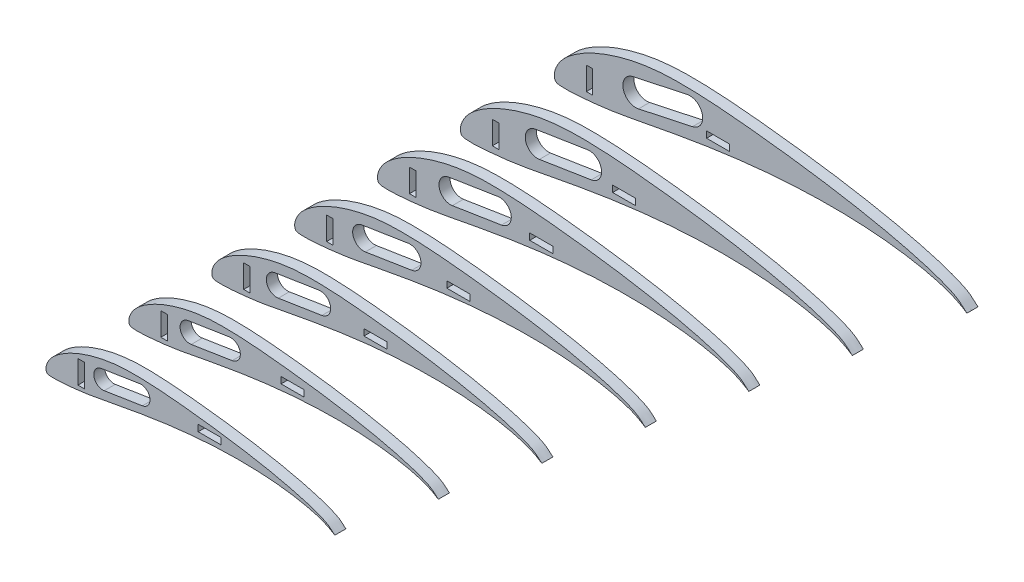
SolidWorks part; units mm, degrees
material "Balsa"
ref_plane "Front Plane" through (0, 0, 0) normal (1, 0, 0) x (0, 1, 0)
ref_plane "Top Plane" through (0, 0, 0) normal (0, 0, 1) x (0, 1, 0)
ref_plane "Right Plane" through (0, 0, 0) normal (0, 1, 0) x (-1, 0, 0)
curve "Curve1"
  spline degree 3 poles (0.9961, 0.0026, 0) (1.0009, -0.0006, 0) (0.9967, 0.0025, 0) (0.9939, 0.0052, 0) (0.9878, 0.0109, 0) (0.9805, 0.017, 0) (0.9705, 0.0231, 0) (0.9581, 0.029, 0) (0.9432, 0.0352, 0) (0.9257, 0.0415, 0) (0.9057, 0.048, 0) (0.8834, 0.0546, 0) (0.8588, 0.0611, 0) (0.8322, 0.0677, 0) (0.8036, 0.0742, 0) (0.7732, 0.0806, 0) (0.7412, 0.0869, 0) (0.7079, 0.0929, 0) (0.6733, 0.0987, 0) (0.6378, 0.1042, 0) (0.6014, 0.1094, 0) (0.5646, 0.1143, 0) (0.5275, 0.1189, 0) (0.4904, 0.1231, 0) (0.4536, 0.1269, 0) (0.4175, 0.1302, 0) (0.3823, 0.1328, 0) (0.3482, 0.1346, 0) (0.3154, 0.1354, 0) (0.284, 0.1353, 0) (0.2541, 0.1338, 0) (0.2258, 0.1307, 0) (0.1988, 0.1263, 0) (0.1732, 0.1206, 0) (0.1489, 0.1139, 0) (0.1262, 0.1063, 0) (0.1051, 0.0981, 0) (0.0858, 0.0892, 0) (0.0682, 0.0798, 0) (0.0525, 0.0701, 0) (0.0388, 0.0602, 0) (0.0271, 0.0502, 0) (0.0176, 0.0401, 0) (0.0103, 0.03, 0) (0.0049, 0.0202, 0) (0.0014, 0.0108, 0) (-0.0002, 0.0022, 0) (0.0001, -0.0051, 0) (0.002, -0.0118, 0) (0.0089, -0.0151, 0) (0.0183, -0.0156, 0) (0.0312, -0.016, 0) (0.0473, -0.0153, 0) (0.0666, -0.0141, 0) (0.0888, -0.012, 0) (0.1137, -0.0092, 0) (0.1411, -0.0057, 0) (0.1711, -0.0007, 0) (0.2038, 0.0055, 0) (0.2393, 0.0123, 0) (0.2775, 0.0195, 0) (0.3182, 0.0267, 0) (0.361, 0.0338, 0) (0.4056, 0.0404, 0) (0.4517, 0.0464, 0) (0.4987, 0.0515, 0) (0.5464, 0.0555, 0) (0.5941, 0.0584, 0) (0.6414, 0.06, 0) (0.6878, 0.0602, 0) (0.7328, 0.059, 0) (0.7758, 0.0564, 0) (0.8164, 0.0525, 0) (0.854, 0.0475, 0) (0.8881, 0.0414, 0) (0.9184, 0.0345, 0) (0.9444, 0.027, 0) (0.9656, 0.0191, 0) (0.9807, 0.0119, 0) (0.9918, 0.0052, 0) (0.9961, 0.0026, 0) (1.0009, -0.0006, 0) (0.9967, 0.0025, 0) knots -0.009748 -0.004147 -0.001 0 0.00098 0.003649 0.007483 0.012095 0.017526 0.024052 0.031783 0.040678 0.05071 0.061833 0.073989 0.087118 0.101145 0.115991 0.13157 0.147788 0.164551 0.181758 0.199312 0.217095 0.23499 0.252857 0.270541 0.287887 0.304773 0.321101 0.336806 0.3518 0.366031 0.379616 0.392653 0.40517 0.417172 0.428604 0.439419 0.449597 0.459102 0.467908 0.475988 0.483309 0.489875 0.495803 0.501149 0.505903 0.510047 0.513579 0.516447 0.51935 0.523823 0.529974 0.537716 0.546968 0.557637 0.56962 0.582804 0.597247 0.613135 0.630444 0.649056 0.668822 0.689595 0.71119 0.733427 0.756094 0.778989 0.80189 0.824567 0.846792 0.868338 0.888978 0.908492 0.926659 0.943286 0.958169 0.971136 0.981956 0.990252 0.995853 0.999 1 1.00098 1.003649 1.007483 periodic
sketch "Sketch2" plane through (0, 0, 0) normal (0, 0, 1) x (0, 1, 0)
  spline S0 degree 3 poles (0.0026, -0.9961) (-0.0006, -1.0009) (0.0025, -0.9967) (0.0052, -0.9939) (0.0109, -0.9878) (0.017, -0.9805) (0.0231, -0.9705) (0.029, -0.9581) (0.0352, -0.9432) (0.0415, -0.9257) (0.048, -0.9057) (0.0546, -0.8834) (0.0611, -0.8588) (0.0677, -0.8322) (0.0742, -0.8036) (0.0806, -0.7732) (0.0869, -0.7412) (0.0929, -0.7079) (0.0987, -0.6733) (0.1042, -0.6378) (0.1094, -0.6014) (0.1143, -0.5646) (0.1189, -0.5275) (0.1231, -0.4904) (0.1269, -0.4536) (0.1302, -0.4175) (0.1328, -0.3823) (0.1346, -0.3482) (0.1354, -0.3154) (0.1353, -0.284) (0.1338, -0.2541) (0.1307, -0.2258) (0.1263, -0.1988) (0.1206, -0.1732) (0.1139, -0.1489) (0.1063, -0.1262) (0.0981, -0.1051) (0.0892, -0.0858) (0.0798, -0.0682) (0.0701, -0.0525) (0.0602, -0.0388) (0.0502, -0.0271) (0.0401, -0.0176) (0.03, -0.0103) (0.0202, -0.0049) (0.0108, -0.0014) (0.0022, 0.0002) (-0.0051, -0.0001) (-0.0118, -0.002) (-0.0151, -0.0089) (-0.0156, -0.0183) (-0.016, -0.0312) (-0.0153, -0.0473) (-0.0141, -0.0666) (-0.012, -0.0888) (-0.0092, -0.1137) (-0.0057, -0.1411) (-0.0007, -0.1711) (0.0055, -0.2038) (0.0123, -0.2393) (0.0195, -0.2775) (0.0267, -0.3182) (0.0338, -0.361) (0.0404, -0.4056) (0.0464, -0.4517) (0.0515, -0.4987) (0.0555, -0.5464) (0.0584, -0.5941) (0.06, -0.6414) (0.0602, -0.6878) (0.059, -0.7328) (0.0564, -0.7758) (0.0525, -0.8164) (0.0475, -0.854) (0.0414, -0.8881) (0.0345, -0.9184) (0.027, -0.9444) (0.0191, -0.9656) (0.0119, -0.9807) (0.0052, -0.9918) (0.0026, -0.9961) (-0.0006, -1.0009) (0.0025, -0.9967) knots -0.009748 -0.004147 -0.001 0 0.00098 0.003649 0.007483 0.012095 0.017526 0.024052 0.031783 0.040678 0.05071 0.061833 0.073989 0.087118 0.101145 0.115991 0.13157 0.147788 0.164551 0.181758 0.199312 0.217095 0.23499 0.252857 0.270541 0.287887 0.304773 0.321101 0.336806 0.3518 0.366031 0.379616 0.392653 0.40517 0.417172 0.428604 0.439419 0.449597 0.459102 0.467908 0.475988 0.483309 0.489875 0.495803 0.501149 0.505903 0.510047 0.513579 0.516447 0.51935 0.523823 0.529974 0.537716 0.546968 0.557637 0.56962 0.582804 0.597247 0.613135 0.630444 0.649056 0.668822 0.689595 0.71119 0.733427 0.756094 0.778989 0.80189 0.824567 0.846792 0.868338 0.888978 0.908492 0.926659 0.943286 0.958169 0.971136 0.981956 0.990252 0.995853 0.999 1 1.00098 1.003649 1.007483 only from (0, -1) to (0, -1) construction
  spline S1 degree 3 poles (0.0026, -0.9961) (-0.0006, -1.0009) (0.0025, -0.9967) (0.0052, -0.9939) (0.0109, -0.9878) (0.017, -0.9805) (0.0231, -0.9705) (0.029, -0.9581) (0.0352, -0.9432) (0.0415, -0.9257) (0.048, -0.9057) (0.0546, -0.8834) (0.0611, -0.8588) (0.0677, -0.8322) (0.0742, -0.8036) (0.0806, -0.7732) (0.0869, -0.7412) (0.0929, -0.7079) (0.0987, -0.6733) (0.1042, -0.6378) (0.1094, -0.6014) (0.1143, -0.5646) (0.1189, -0.5275) (0.1231, -0.4904) (0.1269, -0.4536) (0.1302, -0.4175) (0.1328, -0.3823) (0.1346, -0.3482) (0.1354, -0.3154) (0.1353, -0.284) (0.1338, -0.2541) (0.1307, -0.2258) (0.1263, -0.1988) (0.1206, -0.1732) (0.1139, -0.1489) (0.1063, -0.1262) (0.0981, -0.1051) (0.0892, -0.0858) (0.0798, -0.0682) (0.0701, -0.0525) (0.0602, -0.0388) (0.0502, -0.0271) (0.0401, -0.0176) (0.03, -0.0103) (0.0202, -0.0049) (0.0108, -0.0014) (0.0022, 0.0002) (-0.0051, -0.0001) (-0.0118, -0.002) (-0.0151, -0.0089) (-0.0156, -0.0183) (-0.016, -0.0312) (-0.0153, -0.0473) (-0.0141, -0.0666) (-0.012, -0.0888) (-0.0092, -0.1137) (-0.0057, -0.1411) (-0.0007, -0.1711) (0.0055, -0.2038) (0.0123, -0.2393) (0.0195, -0.2775) (0.0267, -0.3182) (0.0338, -0.361) (0.0404, -0.4056) (0.0464, -0.4517) (0.0515, -0.4987) (0.0555, -0.5464) (0.0584, -0.5941) (0.06, -0.6414) (0.0602, -0.6878) (0.059, -0.7328) (0.0564, -0.7758) (0.0525, -0.8164) (0.0475, -0.854) (0.0414, -0.8881) (0.0345, -0.9184) (0.027, -0.9444) (0.0191, -0.9656) (0.0119, -0.9807) (0.0052, -0.9918) (0.0026, -0.9961) (-0.0006, -1.0009) (0.0025, -0.9967) knots -0.009748 -0.004147 -0.001 0 0.00098 0.003649 0.007483 0.012095 0.017526 0.024052 0.031783 0.040678 0.05071 0.061833 0.073989 0.087118 0.101145 0.115991 0.13157 0.147788 0.164551 0.181758 0.199312 0.217095 0.23499 0.252857 0.270541 0.287887 0.304773 0.321101 0.336806 0.3518 0.366031 0.379616 0.392653 0.40517 0.417172 0.428604 0.439419 0.449597 0.459102 0.467908 0.475988 0.483309 0.489875 0.495803 0.501149 0.505903 0.510047 0.513579 0.516447 0.51935 0.523823 0.529974 0.537716 0.546968 0.557637 0.56962 0.582804 0.597247 0.613135 0.630444 0.649056 0.668822 0.689595 0.71119 0.733427 0.756094 0.778989 0.80189 0.824567 0.846792 0.868338 0.888978 0.908492 0.926659 0.943286 0.958169 0.971136 0.981956 0.990252 0.995853 0.999 1 1.00098 1.003649 1.007483 only from (0, -1) to (0, -1)
  spline S2 degree 3 poles (0.5817, -223.1332) (-0.1446, -224.2031) (0.5543, -223.265) (1.1654, -222.6422) (2.4417, -221.2594) (3.7994, -219.628) (5.1681, -217.3965) (6.4946, -214.6215) (7.8789, -211.2714) (9.3018, -207.3514) (10.7532, -202.8797) (12.2206, -197.8796) (13.697, -192.379) (15.1689, -186.4082) (16.6256, -180.0017) (18.0581, -173.1974) (19.4589, -166.037) (20.8109, -158.5624) (22.1121, -150.8205) (23.3457, -142.856) (24.5142, -134.7205) (25.6083, -126.466) (26.6244, -118.1523) (27.5699, -109.846) (28.4208, -101.6157) (29.1612, -93.5286) (29.7494, -85.6414) (30.154, -77.9993) (30.3288, -70.6447) (30.3102, -63.6154) (29.966, -56.9245) (29.2685, -50.5693) (28.2823, -44.524) (27.0047, -38.7872) (25.5065, -33.3646) (23.8143, -28.2794) (21.9676, -23.553) (19.9763, -19.2149) (17.8809, -15.279) (15.7052, -11.7667) (13.4787, -8.7) (11.2485, -6.0802) (8.9904, -3.9452) (6.7238, -2.3053) (4.5187, -1.094) (2.4251, -0.3176) (0.4927, 0.0523) (-1.1416, -0.0191) (-2.6406, -0.4398) (-3.3847, -2.0039) (-3.4891, -4.1068) (-3.5903, -6.9836) (-3.4343, -10.6014) (-3.1476, -14.9192) (-2.6884, -19.8891) (-2.067, -25.4601) (-1.2702, -31.6052) (-0.1566, -38.3213) (1.2399, -45.641) (2.7597, -53.6011) (4.3644, -62.1626) (5.9874, -71.2717) (7.5678, -80.8615) (9.0528, -90.8576) (10.3879, -101.1739) (11.5342, -111.7177) (12.4404, -122.3892) (13.0827, -133.0814) (13.4358, -143.6827) (13.4805, -154.0779) (13.2135, -164.1512) (12.6412, -173.7872) (11.771, -182.8699) (10.6363, -191.2914) (9.27, -198.9419) (7.7178, -205.7317) (6.0569, -211.5357) (4.2843, -216.2857) (2.6621, -219.6747) (1.1621, -222.1733) (0.5817, -223.1332) (-0.1446, -224.2031) (0.5543, -223.265) knots -0.009748 -0.004147 -0.001 0 0.00098 0.003649 0.007483 0.012095 0.017526 0.024052 0.031783 0.040678 0.05071 0.061833 0.073989 0.087118 0.101145 0.115991 0.13157 0.147788 0.164551 0.181758 0.199312 0.217095 0.23499 0.252857 0.270541 0.287887 0.304773 0.321101 0.336806 0.3518 0.366031 0.379616 0.392653 0.40517 0.417172 0.428604 0.439419 0.449597 0.459102 0.467908 0.475988 0.483309 0.489875 0.495803 0.501149 0.505903 0.510047 0.513579 0.516447 0.51935 0.523823 0.529974 0.537716 0.546968 0.557637 0.56962 0.582804 0.597247 0.613135 0.630444 0.649056 0.668822 0.689595 0.71119 0.733427 0.756094 0.778989 0.80189 0.824567 0.846792 0.868338 0.888978 0.908492 0.926659 0.943286 0.958169 0.971136 0.981956 0.990252 0.995853 0.999 1 1.00098 1.003649 1.007483 only from (0, -224) to (0, -224)
extrude "Boss-Extrude1" add sketch "Sketch2" along normal blind 6 contours S2
sketch "Sketch3" plane through (0, 0, 0) normal (0, 0, -1) x (1, 0, 0)
  line L2 (58.8605, -3.7419) -> (58.8605, -30.0419) construction
  line L7 (44.1949, -13.7419) -> (73.526, -20.0419) construction
  line L8 (45.6649, -6.898) -> (74.996, -13.198)
  line L9 (42.7249, -20.5858) -> (72.056, -26.8858)
  arc A5 (45.6649, -6.898) -> (42.7249, -20.5858) centre (44.1949, -13.7419) ccw
  arc A6 (72.056, -26.8858) -> (74.996, -13.198) centre (73.526, -20.0419) ccw
  spline S0 degree 3 poles (223.265, -0.5543) (224.2031, 0.1446) (223.1332, -0.5817) (222.1733, -1.1621) (219.6747, -2.6621) (216.2857, -4.2843) (211.5357, -6.0569) (205.7317, -7.7178) (198.9419, -9.27) (191.2914, -10.6363) (182.8699, -11.771) (173.7872, -12.6412) (164.1512, -13.2135) (154.0779, -13.4805) (143.6827, -13.4358) (133.0814, -13.0827) (122.3892, -12.4404) (111.7177, -11.5342) (101.1739, -10.3879) (90.8576, -9.0528) (80.8615, -7.5678) (71.2717, -5.9874) (62.1626, -4.3644) (53.6011, -2.7597) (45.641, -1.2399) (38.3213, 0.1566) (31.6052, 1.2702) (25.4601, 2.067) (19.8891, 2.6884) (14.9192, 3.1476) (10.6014, 3.4343) (6.9836, 3.5903) (4.1068, 3.4891) (2.0039, 3.3847) (0.4398, 2.6406) (0.0191, 1.1416) (-0.0523, -0.4927) (0.3176, -2.4251) (1.094, -4.5187) (2.3053, -6.7238) (3.9452, -8.9904) (6.0802, -11.2485) (8.7, -13.4787) (11.7667, -15.7052) (15.279, -17.8809) (19.2149, -19.9763) (23.553, -21.9676) (28.2794, -23.8143) (33.3646, -25.5065) (38.7872, -27.0047) (44.524, -28.2823) (50.5693, -29.2685) (56.9245, -29.966) (63.6154, -30.3102) (70.6447, -30.3288) (77.9993, -30.154) (85.6414, -29.7494) (93.5286, -29.1612) (101.6157, -28.4208) (109.846, -27.5699) (118.1523, -26.6244) (126.466, -25.6083) (134.7205, -24.5142) (142.856, -23.3457) (150.8205, -22.1121) (158.5624, -20.8109) (166.037, -19.4589) (173.1974, -18.0581) (180.0017, -16.6256) (186.4082, -15.1689) (192.379, -13.697) (197.8796, -12.2206) (202.8797, -10.7532) (207.3514, -9.3018) (211.2714, -7.8789) (214.6215, -6.4946) (217.3965, -5.1681) (219.628, -3.7994) (221.2594, -2.4417) (222.6422, -1.1654) (223.265, -0.5543) (224.2031, 0.1446) (223.1332, -0.5817) knots -0.007483 -0.003649 -0.00098 0 0.001 0.004147 0.009748 0.018044 0.028864 0.041831 0.056714 0.073341 0.091508 0.111022 0.131662 0.153208 0.175433 0.19811 0.221011 0.243906 0.266573 0.28881 0.310405 0.331178 0.350944 0.369556 0.386865 0.402753 0.417196 0.43038 0.442363 0.453032 0.462284 0.470026 0.476177 0.48065 0.483553 0.486421 0.489953 0.494097 0.498851 0.504197 0.510125 0.516691 0.524012 0.532092 0.540898 0.550403 0.560581 0.571396 0.582828 0.59483 0.607347 0.620384 0.633969 0.6482 0.663194 0.678899 0.695227 0.712113 0.729459 0.747143 0.76501 0.782905 0.800688 0.818242 0.835449 0.852212 0.86843 0.884009 0.898855 0.912882 0.926011 0.938167 0.94929 0.959322 0.968217 0.975948 0.982474 0.987905 0.992517 0.996351 0.99902 1 1.001 1.004147 1.009748 only from (224, 0) to (224, 0) construction
  point P22 (58.8605, -16.8919)
  dimension "D1" = 10
  dimension "D3" = 30
  dimension "D9" = 7
  dimension "D4" = 26.3
extrude "Cut-Extrude1" cut sketch "Sketch3" against normal blind 10
sketch "Sketch4" plane through (0, 0, 0) normal (0, 0, -1) x (-1, 0, 0)
  point P0 (0, 0)
ref_plane "Plane1" through (-0.0039, 0, 0) normal (-0.9999, 0.0105, 0) x (0, 0, 1)
ref_plane "Plane2" through (0, 0, -45) normal (0, 0, -1) x (-1, 0, 0)
ref_plane "Plane3" through (0, 0, -90) normal (0, 0, -1) x (-1, 0, 0)
ref_plane "Plane4" through (0, 0, -135) normal (0, 0, -1) x (-1, 0, 0)
ref_plane "Plane5" through (0, 0, -180) normal (0, 0, -1) x (-1, 0, 0)
ref_plane "Plane6" through (0, 0, -225) normal (0, 0, -1) x (-1, 0, 0)
ref_plane "Plane7" through (0, 0, -270) normal (0, 0, -1) x (-1, 0, 0)
sketch "Sketch5" plane through (0, 0, -45) normal (0, 0, -1) x (-1, 0, 0)
  line L4 (-40.8046, 20.3934) -> (-68.9559, 24.8385)
  line L5 (-71.0302, 11.7013) -> (-42.879, 7.2561)
  arc A4 (-42.879, 7.2561) -> (-40.8046, 20.3934) centre (-41.8418, 13.8248) ccw
  arc A5 (-68.9559, 24.8385) -> (-71.0302, 11.7013) centre (-69.993, 18.2699) ccw
  spline S2 degree 3 poles (-212.1017, 0.5266) (-212.9929, -0.1374) (-211.9765, 0.5526) (-211.0646, 1.104) (-208.691, 2.529) (-205.4714, 4.0701) (-200.9589, 5.7541) (-195.4451, 7.3319) (-188.9948, 8.8065) (-181.7268, 10.1045) (-173.7264, 11.1825) (-165.0978, 12.0092) (-155.9436, 12.5528) (-146.374, 12.8064) (-136.4985, 12.7641) (-126.4274, 12.4286) (-116.2697, 11.8183) (-106.1318, 10.9575) (-96.1152, 9.8685) (-86.3147, 8.6001) (-76.8184, 7.1894) (-67.7081, 5.688) (-59.0545, 4.1462) (-50.9211, 2.6217) (-43.359, 1.1779) (-36.4052, -0.1488) (-30.0249, -1.2067) (-24.1871, -1.9637) (-18.8946, -2.554) (-14.1732, -2.9902) (-10.0713, -3.2626) (-6.6344, -3.4108) (-3.9015, -3.3146) (-1.9037, -3.2155) (-0.4179, -2.5086) (-0.0181, -1.0846) (0.0497, 0.4681) (-0.3017, 2.3039) (-1.0393, 4.2928) (-2.19, 6.3876) (-3.748, 8.5408) (-5.7762, 10.6861) (-8.265, 12.8047) (-11.1783, 14.9199) (-14.5151, 16.9869) (-18.2542, 18.9775) (-22.3754, 20.8692) (-26.8654, 22.6236) (-31.6964, 24.2312) (-36.8478, 25.6545) (-42.2978, 26.8682) (-48.0408, 27.8051) (-54.0783, 28.4677) (-60.4347, 28.7947) (-67.1125, 28.8123) (-74.0993, 28.6463) (-81.3593, 28.2619) (-88.8521, 27.7031) (-96.5349, 26.9997) (-104.3537, 26.1914) (-112.2447, 25.2932) (-120.1427, 24.3278) (-127.9845, 23.2885) (-135.7132, 22.1784) (-143.2795, 21.0065) (-150.6342, 19.7704) (-157.7352, 18.486) (-164.5375, 17.1552) (-171.0016, 15.7943) (-177.0878, 14.4104) (-182.76, 13.0121) (-187.9856, 11.6095) (-192.7358, 10.2156) (-196.9839, 8.8367) (-200.7079, 7.4849) (-203.8904, 6.1698) (-206.5267, 4.9097) (-208.6466, 3.6094) (-210.1964, 2.3196) (-211.5101, 1.1071) (-212.1017, 0.5266) (-212.9929, -0.1374) (-211.9765, 0.5526) knots -0.007483 -0.003649 -0.00098 0 0.001 0.004147 0.009748 0.018044 0.028864 0.041831 0.056714 0.073341 0.091508 0.111022 0.131662 0.153208 0.175433 0.19811 0.221011 0.243906 0.266573 0.28881 0.310405 0.331178 0.350944 0.369556 0.386865 0.402753 0.417196 0.43038 0.442363 0.453032 0.462284 0.470026 0.476177 0.48065 0.483553 0.486421 0.489953 0.494097 0.498851 0.504197 0.510125 0.516691 0.524012 0.532092 0.540898 0.550403 0.560581 0.571396 0.582828 0.59483 0.607347 0.620384 0.633969 0.6482 0.663194 0.678899 0.695227 0.712113 0.729459 0.747143 0.76501 0.782905 0.800688 0.818242 0.835449 0.852212 0.86843 0.884009 0.898855 0.912882 0.926011 0.938167 0.94929 0.959322 0.968217 0.975948 0.982474 0.987905 0.992517 0.996351 0.99902 1 1.001 1.004147 1.009748 only from (-212.8, 0) to (-212.8, 0)
sketch "Sketch6" plane through (0, 0, -90) normal (0, 0, -1) x (-1, 0, 0)
  line L4 (-38.657, 19.32) -> (-65.3266, 23.5312)
  line L5 (-67.2918, 11.0854) -> (-40.6222, 6.8742)
  arc A4 (-40.6222, 6.8742) -> (-38.657, 19.32) centre (-39.6396, 13.0971) ccw
  arc A5 (-65.3266, 23.5312) -> (-67.2918, 11.0854) centre (-66.3092, 17.3083) ccw
  spline S2 degree 3 poles (-200.9385, 0.4989) (-201.7828, -0.1301) (-200.8198, 0.5235) (-199.956, 1.0459) (-197.7072, 2.3959) (-194.6571, 3.8559) (-190.3821, 5.4512) (-185.1585, 6.946) (-179.0477, 8.343) (-172.1623, 9.5727) (-164.5829, 10.5939) (-156.4085, 11.3771) (-147.7361, 11.8921) (-138.6701, 12.1324) (-129.3144, 12.0923) (-119.7733, 11.7744) (-110.1503, 11.1963) (-100.5459, 10.3808) (-91.0565, 9.3491) (-81.7719, 8.1475) (-72.7753, 6.811) (-64.1445, 5.3887) (-55.9463, 3.928) (-48.241, 2.4837) (-41.0769, 1.1159) (-34.4891, -0.1409) (-28.4447, -1.1432) (-22.9141, -1.8603) (-17.9002, -2.4195) (-13.4273, -2.8328) (-9.5412, -3.0908) (-6.2853, -3.2313) (-3.6961, -3.1402) (-1.8035, -3.0462) (-0.3959, -2.3766) (-0.0172, -1.0275) (0.0471, 0.4434) (-0.2858, 2.1826) (-0.9846, 4.0668) (-2.0748, 6.0514) (-3.5507, 8.0913) (-5.4721, 10.1237) (-7.83, 12.1308) (-10.59, 14.1347) (-13.7511, 16.0928) (-17.2934, 17.9787) (-21.1977, 19.7708) (-25.4514, 21.4328) (-30.0282, 22.9559) (-34.9084, 24.3042) (-40.0716, 25.4541) (-45.5124, 26.3417) (-51.232, 26.9694) (-57.2539, 27.2792) (-63.5803, 27.2959) (-70.1994, 27.1386) (-77.0773, 26.7745) (-84.1757, 26.2451) (-91.4542, 25.5787) (-98.8614, 24.8129) (-106.3371, 23.962) (-113.8194, 23.0474) (-121.2484, 22.0628) (-128.5704, 21.0111) (-135.7384, 19.9009) (-142.7061, 18.7298) (-149.4333, 17.513) (-155.8777, 16.2523) (-162.0015, 14.9631) (-167.7674, 13.652) (-173.1411, 12.3273) (-178.0916, 10.9985) (-182.5918, 9.6779) (-186.6163, 8.3716) (-190.1443, 7.091) (-193.1593, 5.8451) (-195.6568, 4.6513) (-197.6652, 3.4194) (-199.1335, 2.1975) (-200.378, 1.0488) (-200.9385, 0.4989) (-201.7828, -0.1301) (-200.8198, 0.5235) knots -0.007483 -0.003649 -0.00098 0 0.001 0.004147 0.009748 0.018044 0.028864 0.041831 0.056714 0.073341 0.091508 0.111022 0.131662 0.153208 0.175433 0.19811 0.221011 0.243906 0.266573 0.28881 0.310405 0.331178 0.350944 0.369556 0.386865 0.402753 0.417196 0.43038 0.442363 0.453032 0.462284 0.470026 0.476177 0.48065 0.483553 0.486421 0.489953 0.494097 0.498851 0.504197 0.510125 0.516691 0.524012 0.532092 0.540898 0.550403 0.560581 0.571396 0.582828 0.59483 0.607347 0.620384 0.633969 0.6482 0.663194 0.678899 0.695227 0.712113 0.729459 0.747143 0.76501 0.782905 0.800688 0.818242 0.835449 0.852212 0.86843 0.884009 0.898855 0.912882 0.926011 0.938167 0.94929 0.959322 0.968217 0.975948 0.982474 0.987905 0.992517 0.996351 0.99902 1 1.001 1.004147 1.009748 only from (-201.6, 0) to (-201.6, 0)
sketch "Sketch7" plane through (0, 0, -135) normal (0, 0, -1) x (-1, 0, 0)
  line L4 (-36.5094, 18.2467) -> (-61.6973, 22.2239)
  line L5 (-63.5534, 10.4696) -> (-38.3654, 6.4923)
  arc A4 (-38.3654, 6.4923) -> (-36.5094, 18.2467) centre (-37.4374, 12.3695) ccw
  arc A5 (-61.6973, 22.2239) -> (-63.5534, 10.4696) centre (-62.6254, 16.3467) ccw
  spline S2 degree 3 poles (-189.7752, 0.4712) (-190.5726, -0.1229) (-189.6632, 0.4944) (-188.8473, 0.9878) (-186.7235, 2.2628) (-183.8428, 3.6416) (-179.8053, 5.1484) (-174.8719, 6.5601) (-169.1006, 7.8795) (-162.5977, 9.0409) (-155.4395, 10.0054) (-147.7191, 10.745) (-139.5285, 11.2315) (-130.9662, 11.4584) (-122.1303, 11.4205) (-113.1192, 11.1203) (-104.0308, 10.5743) (-94.96, 9.8041) (-85.9979, 8.8297) (-77.229, 7.6948) (-68.7323, 6.4326) (-60.5809, 5.0893) (-52.8382, 3.7097) (-45.5609, 2.3457) (-38.7949, 1.0539) (-32.5731, -0.1331) (-26.8644, -1.0797) (-21.6411, -1.757) (-16.9057, -2.2851) (-12.6813, -2.6754) (-9.0112, -2.9191) (-5.9361, -3.0517) (-3.4908, -2.9657) (-1.7033, -2.877) (-0.3739, -2.2445) (-0.0162, -0.9704) (0.0445, 0.4188) (-0.27, 2.0613) (-0.9299, 3.8409) (-1.9595, 5.7152) (-3.3534, 7.6418) (-5.1681, 9.5612) (-7.395, 11.4569) (-10.0017, 13.3494) (-12.9872, 15.1988) (-16.3327, 16.9799) (-20.0201, 18.6724) (-24.0375, 20.2421) (-28.3599, 21.6805) (-32.9691, 22.954) (-37.8454, 24.04) (-42.9839, 24.8783) (-48.3858, 25.4711) (-54.0731, 25.7637) (-60.048, 25.7795) (-66.2994, 25.6309) (-72.7952, 25.287) (-79.4993, 24.787) (-86.3734, 24.1577) (-93.3691, 23.4344) (-100.4295, 22.6308) (-107.4961, 21.767) (-114.5124, 20.8371) (-121.4276, 19.8439) (-128.1974, 18.7953) (-134.778, 17.6893) (-141.1315, 16.5401) (-147.2178, 15.3494) (-153.0014, 14.1318) (-158.447, 12.8936) (-163.5221, 11.6424) (-168.1976, 10.3875) (-172.4478, 9.1402) (-176.2487, 7.9065) (-179.5807, 6.697) (-182.4283, 5.5204) (-184.787, 4.3929) (-186.6838, 3.2295) (-188.0705, 2.0754) (-189.2459, 0.9906) (-189.7752, 0.4712) (-190.5726, -0.1229) (-189.6632, 0.4944) knots -0.007483 -0.003649 -0.00098 0 0.001 0.004147 0.009748 0.018044 0.028864 0.041831 0.056714 0.073341 0.091508 0.111022 0.131662 0.153208 0.175433 0.19811 0.221011 0.243906 0.266573 0.28881 0.310405 0.331178 0.350944 0.369556 0.386865 0.402753 0.417196 0.43038 0.442363 0.453032 0.462284 0.470026 0.476177 0.48065 0.483553 0.486421 0.489953 0.494097 0.498851 0.504197 0.510125 0.516691 0.524012 0.532092 0.540898 0.550403 0.560581 0.571396 0.582828 0.59483 0.607347 0.620384 0.633969 0.6482 0.663194 0.678899 0.695227 0.712113 0.729459 0.747143 0.76501 0.782905 0.800688 0.818242 0.835449 0.852212 0.86843 0.884009 0.898855 0.912882 0.926011 0.938167 0.94929 0.959322 0.968217 0.975948 0.982474 0.987905 0.992517 0.996351 0.99902 1 1.001 1.004147 1.009748 only from (-190.4, 0) to (-190.4, 0)
sketch "Sketch8" plane through (0, 0, -180) normal (0, 0, -1) x (-1, 0, 0)
  line L4 (-34.3618, 17.1734) -> (-58.0681, 20.9166)
  line L5 (-59.8149, 9.8537) -> (-36.1087, 6.1104)
  arc A4 (-36.1087, 6.1104) -> (-34.3618, 17.1734) centre (-35.2352, 11.6419) ccw
  arc A5 (-58.0681, 20.9166) -> (-59.8149, 9.8537) centre (-58.9415, 15.3852) ccw
  spline S2 degree 3 poles (-178.612, 0.4435) (-179.3625, -0.1157) (-178.5065, 0.4654) (-177.7386, 0.9297) (-175.7397, 2.1297) (-173.0286, 3.4274) (-169.2286, 4.8455) (-164.5854, 6.1742) (-159.1535, 7.416) (-153.0331, 8.509) (-146.296, 9.4168) (-139.0297, 10.113) (-131.321, 10.5708) (-123.2623, 10.7844) (-114.9461, 10.7487) (-106.4651, 10.4662) (-97.9114, 9.9523) (-89.3741, 9.2274) (-80.9392, 8.3103) (-72.6861, 7.2422) (-64.6892, 6.0542) (-57.0173, 4.7899) (-49.7301, 3.4915) (-42.8809, 2.2078) (-36.5128, 0.9919) (-30.657, -0.1253) (-25.2841, -1.0162) (-20.3681, -1.6536) (-15.9113, -2.1507) (-11.9354, -2.5181) (-8.4811, -2.7474) (-5.5869, -2.8722) (-3.2855, -2.7913) (-1.6031, -2.7078) (-0.3519, -2.1125) (-0.0153, -0.9133) (0.0419, 0.3942) (-0.2541, 1.9401) (-0.8752, 3.615) (-1.8442, 5.379) (-3.1562, 7.1923) (-4.8641, 8.9988) (-6.96, 10.7829) (-9.4133, 12.5642) (-12.2232, 14.3047) (-15.3719, 15.9811) (-18.8424, 17.5741) (-22.6235, 19.0514) (-26.6917, 20.4052) (-31.0297, 21.6038) (-35.6192, 22.6259) (-40.4554, 23.4148) (-45.5396, 23.9728) (-50.8924, 24.2481) (-56.5158, 24.263) (-62.3994, 24.1232) (-68.5131, 23.7995) (-74.8229, 23.3289) (-81.2926, 22.7366) (-87.8768, 22.0559) (-94.5219, 21.2995) (-101.1728, 20.4866) (-107.7764, 19.6114) (-114.2848, 18.6766) (-120.6564, 17.6897) (-126.8499, 16.6487) (-132.8296, 15.5672) (-138.5579, 14.4465) (-144.0013, 13.3005) (-149.1266, 12.1351) (-153.9032, 10.9576) (-158.3037, 9.7765) (-162.3038, 8.6026) (-165.8811, 7.4414) (-169.0172, 6.3031) (-171.6972, 5.1957) (-173.9172, 4.1345) (-175.7024, 3.0395) (-177.0075, 1.9533) (-178.1138, 0.9323) (-178.612, 0.4435) (-179.3625, -0.1157) (-178.5065, 0.4654) knots -0.007483 -0.003649 -0.00098 0 0.001 0.004147 0.009748 0.018044 0.028864 0.041831 0.056714 0.073341 0.091508 0.111022 0.131662 0.153208 0.175433 0.19811 0.221011 0.243906 0.266573 0.28881 0.310405 0.331178 0.350944 0.369556 0.386865 0.402753 0.417196 0.43038 0.442363 0.453032 0.462284 0.470026 0.476177 0.48065 0.483553 0.486421 0.489953 0.494097 0.498851 0.504197 0.510125 0.516691 0.524012 0.532092 0.540898 0.550403 0.560581 0.571396 0.582828 0.59483 0.607347 0.620384 0.633969 0.6482 0.663194 0.678899 0.695227 0.712113 0.729459 0.747143 0.76501 0.782905 0.800688 0.818242 0.835449 0.852212 0.86843 0.884009 0.898855 0.912882 0.926011 0.938167 0.94929 0.959322 0.968217 0.975948 0.982474 0.987905 0.992517 0.996351 0.99902 1 1.001 1.004147 1.009748 only from (-179.2, 0) to (-179.2, 0)
sketch "Sketch9" plane through (0, 0, -225) normal (0, 0, -1) x (-1, 0, 0)
  line L4 (-32.2142, 16.1) -> (-54.4388, 19.6093)
  line L5 (-56.0765, 9.2378) -> (-33.8519, 5.7285)
  arc A4 (-33.8519, 5.7285) -> (-32.2142, 16.1) centre (-33.033, 10.9143) ccw
  arc A5 (-54.4388, 19.6093) -> (-56.0765, 9.2378) centre (-55.2577, 14.4236) ccw
  spline S2 degree 3 poles (-167.4487, 0.4158) (-168.1523, -0.1084) (-167.3499, 0.4363) (-166.63, 0.8716) (-164.756, 1.9966) (-162.2143, 3.2132) (-158.6518, 4.5427) (-154.2988, 5.7884) (-149.2064, 6.9525) (-143.4685, 7.9772) (-137.1525, 8.8283) (-130.3404, 9.4809) (-123.1134, 9.9101) (-115.5584, 10.1103) (-107.762, 10.0769) (-99.8111, 9.812) (-91.7919, 9.3303) (-83.7882, 8.6507) (-75.8805, 7.7909) (-68.1432, 6.7896) (-60.6461, 5.6758) (-53.4538, 4.4906) (-46.6219, 3.2733) (-40.2008, 2.0698) (-34.2308, 0.9299) (-28.7409, -0.1175) (-23.7039, -0.9527) (-19.0951, -1.5503) (-14.9168, -2.0163) (-11.1894, -2.3607) (-7.951, -2.5757) (-5.2377, -2.6927) (-3.0801, -2.6168) (-1.5029, -2.5385) (-0.3299, -1.9805) (-0.0143, -0.8562) (0.0392, 0.3695) (-0.2382, 1.8188) (-0.8205, 3.389) (-1.729, 5.0428) (-2.9589, 6.7428) (-4.5601, 8.4364) (-6.525, 10.109) (-8.825, 11.7789) (-11.4593, 13.4107) (-14.4112, 14.9822) (-17.6648, 16.4757) (-21.2095, 17.8607) (-25.0235, 19.1299) (-29.0904, 20.2535) (-33.393, 21.2118) (-37.927, 21.9514) (-42.6934, 22.4745) (-47.7116, 22.7326) (-52.9836, 22.7466) (-58.4995, 22.6155) (-64.2311, 22.3121) (-70.1464, 21.8709) (-76.2118, 21.3156) (-82.3845, 20.6774) (-88.6143, 19.9683) (-94.8495, 19.2062) (-101.0404, 18.3856) (-107.142, 17.5093) (-113.1154, 16.5841) (-118.9218, 15.6082) (-124.5278, 14.5942) (-129.898, 13.5436) (-135.0012, 12.4692) (-139.8062, 11.3767) (-144.2842, 10.2727) (-148.4097, 9.1654) (-152.1598, 8.0649) (-155.5136, 6.9763) (-158.4536, 5.9092) (-160.9661, 4.8709) (-163.0474, 3.8761) (-164.721, 2.8495) (-165.9446, 1.8312) (-166.9817, 0.874) (-167.4487, 0.4158) (-168.1523, -0.1084) (-167.3499, 0.4363) knots -0.007483 -0.003649 -0.00098 0 0.001 0.004147 0.009748 0.018044 0.028864 0.041831 0.056714 0.073341 0.091508 0.111022 0.131662 0.153208 0.175433 0.19811 0.221011 0.243906 0.266573 0.28881 0.310405 0.331178 0.350944 0.369556 0.386865 0.402753 0.417196 0.43038 0.442363 0.453032 0.462284 0.470026 0.476177 0.48065 0.483553 0.486421 0.489953 0.494097 0.498851 0.504197 0.510125 0.516691 0.524012 0.532092 0.540898 0.550403 0.560581 0.571396 0.582828 0.59483 0.607347 0.620384 0.633969 0.6482 0.663194 0.678899 0.695227 0.712113 0.729459 0.747143 0.76501 0.782905 0.800688 0.818242 0.835449 0.852212 0.86843 0.884009 0.898855 0.912882 0.926011 0.938167 0.94929 0.959322 0.968217 0.975948 0.982474 0.987905 0.992517 0.996351 0.99902 1 1.001 1.004147 1.009748 only from (-168, 0) to (-168, 0)
sketch "Sketch10" plane through (0, 0, -270) normal (0, 0, -1) x (-1, 0, 0)
  line L4 (-30.0666, 15.0267) -> (-50.8096, 18.3021)
  line L5 (-52.3381, 8.622) -> (-31.5951, 5.3466)
  arc A4 (-31.5951, 5.3466) -> (-30.0666, 15.0267) centre (-30.8308, 10.1867) ccw
  arc A5 (-50.8096, 18.3021) -> (-52.3381, 8.622) centre (-51.5738, 13.462) ccw
  spline S2 degree 3 poles (-156.2855, 0.388) (-156.9421, -0.1012) (-156.1932, 0.4072) (-155.5213, 0.8135) (-153.7723, 1.8635) (-151.4, 2.999) (-148.075, 4.2398) (-144.0122, 5.4025) (-139.2593, 6.489) (-133.904, 7.4454) (-128.009, 8.2397) (-121.651, 8.8489) (-114.9058, 9.2494) (-107.8545, 9.4363) (-100.5779, 9.4051) (-93.157, 9.1579) (-85.6724, 8.7083) (-78.2024, 8.074) (-70.8218, 7.2715) (-63.6003, 6.3369) (-56.603, 5.2974) (-49.8902, 4.1912) (-43.5138, 3.0551) (-37.5208, 1.9318) (-31.9487, 0.8679) (-26.8249, -0.1096) (-22.1236, -0.8892) (-17.8221, -1.4469) (-13.9224, -1.8819) (-10.4434, -2.2033) (-7.421, -2.404) (-4.8885, -2.5132) (-2.8748, -2.4424) (-1.4027, -2.3693) (-0.3079, -1.8484) (-0.0134, -0.7992) (0.0366, 0.3449) (-0.2223, 1.6976) (-0.7658, 3.1631) (-1.6137, 4.7066) (-2.7617, 6.2932) (-4.2561, 7.874) (-6.09, 9.4351) (-8.2367, 10.9936) (-10.6953, 12.5166) (-13.4504, 13.9834) (-16.4871, 15.3773) (-19.7956, 16.67) (-23.3552, 17.8546) (-27.151, 18.9033) (-31.1668, 19.7976) (-35.3985, 20.488) (-39.8471, 20.9762) (-44.5308, 21.2171) (-49.4513, 21.2301) (-54.5995, 21.1078) (-59.949, 20.8246) (-65.47, 20.4128) (-71.131, 19.8945) (-76.8922, 19.2989) (-82.7066, 18.6371) (-88.5262, 17.9258) (-94.3043, 17.1599) (-99.9992, 16.342) (-105.5743, 15.4785) (-110.9936, 14.5676) (-116.2259, 13.6213) (-121.2382, 12.6407) (-126.0012, 11.6379) (-130.4858, 10.6182) (-134.6653, 9.5879) (-138.5157, 8.5544) (-142.0158, 7.5272) (-145.146, 6.5112) (-147.89, 5.5152) (-150.235, 4.5462) (-152.1775, 3.6177) (-153.7396, 2.6596) (-154.8816, 1.7092) (-155.8495, 0.8158) (-156.2855, 0.388) (-156.9421, -0.1012) (-156.1932, 0.4072) knots -0.007483 -0.003649 -0.00098 0 0.001 0.004147 0.009748 0.018044 0.028864 0.041831 0.056714 0.073341 0.091508 0.111022 0.131662 0.153208 0.175433 0.19811 0.221011 0.243906 0.266573 0.28881 0.310405 0.331178 0.350944 0.369556 0.386865 0.402753 0.417196 0.43038 0.442363 0.453032 0.462284 0.470026 0.476177 0.48065 0.483553 0.486421 0.489953 0.494097 0.498851 0.504197 0.510125 0.516691 0.524012 0.532092 0.540898 0.550403 0.560581 0.571396 0.582828 0.59483 0.607347 0.620384 0.633969 0.6482 0.663194 0.678899 0.695227 0.712113 0.729459 0.747143 0.76501 0.782905 0.800688 0.818242 0.835449 0.852212 0.86843 0.884009 0.898855 0.912882 0.926011 0.938167 0.94929 0.959322 0.968217 0.975948 0.982474 0.987905 0.992517 0.996351 0.99902 1 1.001 1.004147 1.009748 only from (-156.8, 0) to (-156.8, 0)
extrude "Boss-Extrude8" add sketch "Sketch5" along normal blind 6 separate body
extrude "Boss-Extrude9" add sketch "Sketch6" along normal blind 6 separate body
extrude "Boss-Extrude10" add sketch "Sketch7" along normal blind 6 separate body
extrude "Boss-Extrude11" add sketch "Sketch8" along normal blind 6 separate body
extrude "Boss-Extrude12" add sketch "Sketch9" along normal blind 6 separate body
extrude "Boss-Extrude13" add sketch "Sketch10" along normal blind 6 separate body
sketch "Sketch11" plane through (0, 0, 6) normal (0, 0, 1) x (1, 0, 0)
  line L1 (20.8281, 13.3439) -> (17.3281, 13.3439)
  line L2 (20.8281, 13.3439) -> (20.8281, 0.8439)
  line L3 (20.8281, 0.8439) -> (17.3281, 0.8439)
  line L4 (17.3281, 13.3439) -> (17.3281, 0.8439)
  line L5 (20.8281, 13.3439) -> (17.3281, 0.8439) construction
  line L6 (20.8281, 0.8439) -> (17.3281, 13.3439) construction
  line L7 (95.1354, 15.0727) -> (82.6354, 15.0727)
  line L8 (95.1354, 15.0727) -> (95.1354, 11.5727)
  line L9 (95.1354, 11.5727) -> (82.6354, 11.5727)
  line L10 (82.6354, 15.0727) -> (82.6354, 11.5727)
  line L11 (95.1354, 15.0727) -> (82.6354, 11.5727) construction
  line L12 (95.1354, 11.5727) -> (82.6354, 15.0727) construction
  point P1 (19.0781, 7.0939)
  point P7 (88.8854, 13.3227)
extrude "Cut-Extrude2" cut sketch "Sketch11" against normal through all contours L2 L1 L4 L3 | L8 L7 L10 L9
ref_plane "Plane12" through (0, 0, 16) normal (0, 0, 1) x (1, 0, 0)
mirror "Mirror3" about plane through (0, 0, 16) normal (0, 0, 1) of bodies 158 161 155 160 159 157 156
delete or keep bodies "Body-Delete/Keep 1" type delete bodies bodies 157 159 158
delete or keep bodies "Body-Delete/Keep 2" type delete bodies bodies 156 160 161
delete or keep bodies "Body-Delete/Keep 3" type delete bodies bodies 155
